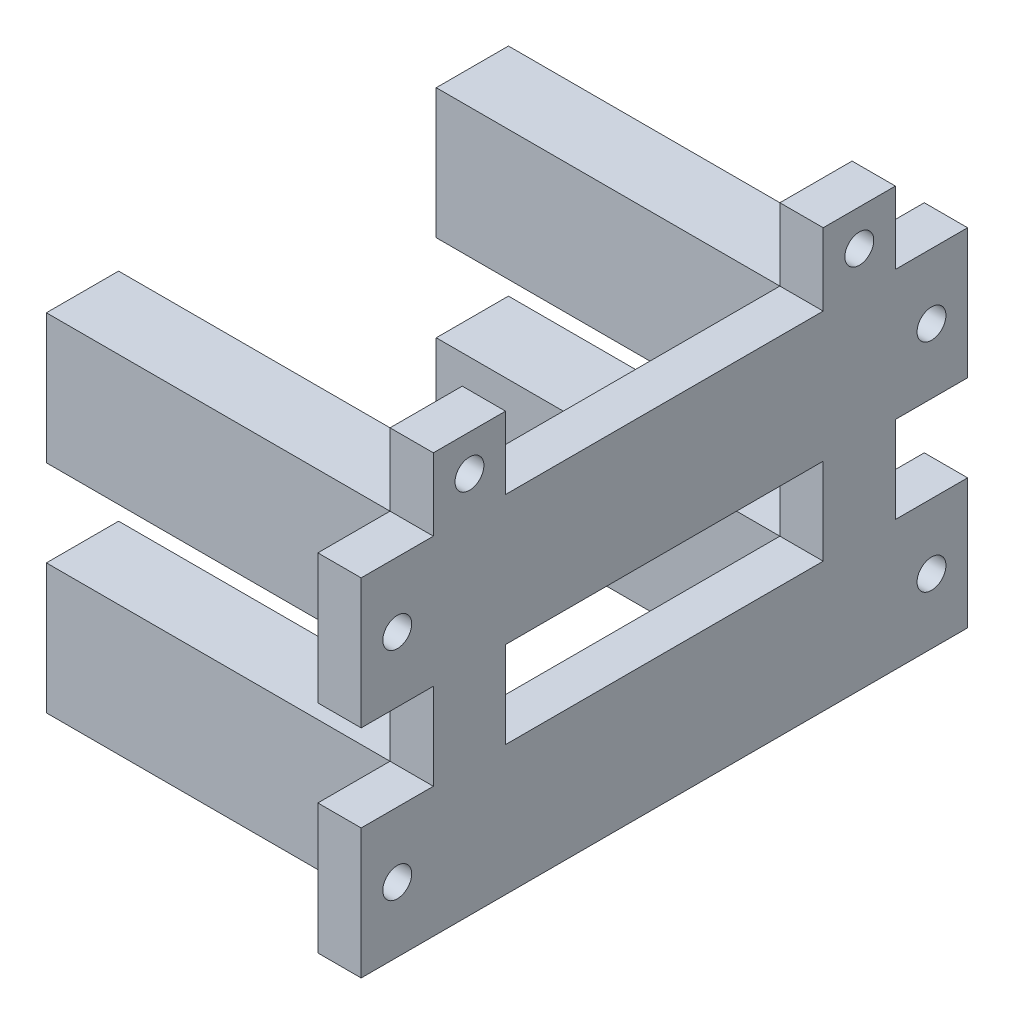
SolidWorks part; units mm, degrees
ref_plane "前视基准面" through (0, 0, 0) normal (0, 0, 1) x (1, 0, 0)
ref_plane "上视基准面" through (0, 0, 0) normal (0, 1, 0) x (1, 0, 0)
ref_plane "右视基准面" through (0, 0, 0) normal (1, 0, 0) x (0, 0, -1)
other "Configuration Table"
sketch "草图1" plane through (0, 0, 0) normal (1, 0, 0) x (0, 0, -1)
  line L5 (-16, -12) -> (16, -12)
  line L6 (-16, -12) -> (-16, 12)
  line L7 (-16, 12) -> (16, 12)
  line L8 (16, -12) -> (16, 12)
  line L9 (-16, -12) -> (16, 12) construction
  line L10 (-16, 12) -> (16, -12) construction
  point P0 (0, 0)
  dimension "D1" = 32
  dimension "D3" = 24
extrude "凸台-拉伸1" add sketch "草图1" along normal blind 23.8
sketch "草图7" plane through (0, 0, 0) normal (-1, 0, 0) x (0, 0, 1)
  line L0 (13.5, 7.5) -> (-13.5, -7.5) construction
  line L1 (-13.5, 7.5) -> (13.5, -7.5) construction
  circle A0 centre (13.5, 7.5) radius 1.75
  circle A1 centre (13.5, -7.5) radius 1.75
  circle A2 centre (-13.5, 7.5) radius 1.75
  circle A3 centre (-13.5, -7.5) radius 1.75
  circle A4 centre (13.5, 7.5) radius 0.65
  circle A5 centre (13.5, -7.5) radius 0.65
  circle A6 centre (-13.5, -7.5) radius 0.65
  circle A7 centre (-13.5, 7.5) radius 0.65
  dimension "D1" = 1.3
  dimension "D2" = 3.5
  dimension "D3" = 15
  dimension "D4" = 27
extrude "切除-拉伸1" cut sketch "草图7" against normal blind 2 contours A7 | A6 | A4 | A5
sketch "草图8" plane through (0, 0, 0) normal (-1, 0, 0) x (0, 0, 1)
  line L0 (16, -12) -> (-16, -12) construction
  line L1 (-16, -12) -> (-11, -12)
  line L2 (-16, -12) -> (-16, -3)
  line L3 (-16, -3) -> (-11, -3)
  line L4 (-11, -12) -> (-11, -3)
  line L5 (-16, 12) -> (16, 12) construction
  line L6 (-16, 12) -> (-11, 12)
  line L7 (-16, 12) -> (-16, 3)
  line L8 (-16, 3) -> (-11, 3)
  line L9 (-11, 12) -> (-11, 3)
  line L10 (-16, -12) -> (-16, 12) construction
  line L11 (16, 12) -> (16, -12) construction
  line L12 (16, -12) -> (11, -12)
  line L13 (16, -12) -> (16, -3)
  line L14 (16, -3) -> (11, -3)
  line L15 (11, -12) -> (11, -3)
  line L16 (-16, -7.5) -> (-13.5, -7.5) construction
  line L17 (16, 12) -> (11, 12)
  line L18 (16, 12) -> (16, 3)
  line L19 (16, 3) -> (11, 3)
  line L20 (11, 12) -> (11, 3)
  line L21 (-13.5, -7.5) -> (-11, -7.5) construction
  line L22 (-13.5, -12) -> (-13.5, -7.5) construction
  line L23 (-13.5, -3) -> (-13.5, -7.5) construction
  circle A0 centre (-13.5, -7.5) radius 0.65 construction
  point P29 (0, 0)
  point P30 (0, 0)
  point P31 (0, 0)
extrude "切除-拉伸2" cut sketch "草图8" against normal through all flip side to cut
sketch "草图9" plane through (23.8, 0, 0) normal (1, 0, 0) x (0, 0, -1)
  line L0 (11, -12) -> (11, -3) construction
  line L1 (-16, -12) -> (-11, -12)
  line L2 (-16, -12) -> (-16, 17)
  line L3 (-16, 17) -> (-11, 17)
  line L4 (-11, -12) -> (-11, 17)
  line L5 (11, -12) -> (16, -12)
  line L6 (11, -12) -> (11, 17)
  line L7 (11, 17) -> (16, 17)
  line L8 (16, -12) -> (16, 17)
  line L9 (16, -12) -> (16, -3) construction
  line L10 (-11, -3) -> (-11, -12) construction
  line L12 (-16, -12) -> (-11, -12) construction
  line L13 (-11, 12) -> (-16, 12) construction
  line L14 (-16, -3) -> (-11, -3) construction
  line L15 (-21, 12) -> (21, 12)
  line L16 (-21, 12) -> (-21, 3)
  line L17 (-21, 3) -> (21, 3)
  line L18 (21, 12) -> (21, 3)
  line L19 (21, -3) -> (-21, -3)
  line L20 (21, -3) -> (21, -12)
  line L21 (21, -12) -> (-21, -12)
  line L22 (-21, -3) -> (-21, -12)
  line L23 (-11, 3) -> (-16, 3) construction
  line L24 (-16, 17) -> (-11, 12) construction
  line L25 (-21, 12) -> (-16, 3)
  line L26 (-21, -3) -> (-16, -12)
  line L29 (16, -12) -> (21, -3)
  line L30 (21, 3) -> (16, 12)
  line L31 (16, 12) -> (11, 17)
  circle A1 centre (-13.5, 14.5) radius 1
  circle A2 centre (13.5, 14.5) radius 1
  circle A6 centre (18.5, -7.5) radius 1
  circle A7 centre (18.5, 7.5) radius 1
  circle A8 centre (-18.5, 7.5) radius 1
  circle A9 centre (-18.5, -7.5) radius 1
  point P38 (16, 13.1829)
  point P39 (0, 0)
  dimension "D7" = 2
  dimension "D2" = 5
  dimension "D3" = 5
  dimension "D5" = 5
  dimension "D6" = 5
extrude "凸台-拉伸2" add sketch "草图9" along normal blind 3
sketch "草图11" plane through (23.8, 0, 0) normal (-1, 0, 0) x (0, 0, 1)
  circle A0 centre (-18.5, -7.5) radius 1.75
  circle A1 centre (-13.5, -14.5) radius 1.75
  circle A2 centre (-18.547, 7.5) radius 1.75
  circle A3 centre (13.5, -14.5) radius 1.75
  circle A4 centre (18.5, -7.5) radius 1.75
  circle A5 centre (18.5, 7.5) radius 1.75
  circle A6 centre (13.5, 14.5) radius 1.75
  circle A7 centre (-13.5, 14.5) radius 1.75
  point P16 (0, 0)
  point P17 (0, 0)
  point P18 (0, 0)
  point P19 (0, 0)
  point P20 (0, 0)
  dimension "D1" = 3.5
extrude "切除-拉伸3" cut sketch "草图11" against normal blind 1.5
